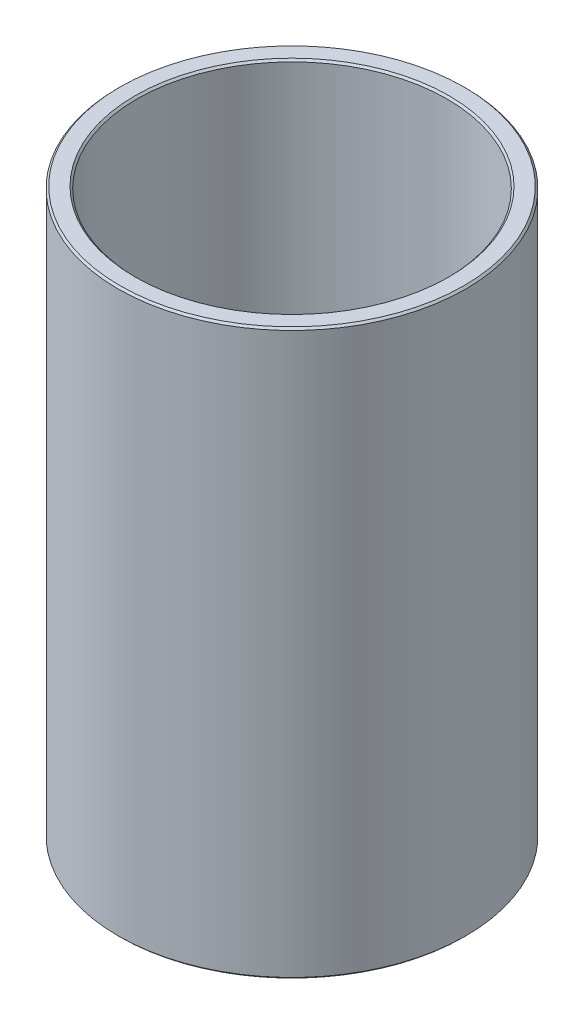
SolidWorks part; units mm, degrees
material "1.4305 (X8CrNiS18-9)"
ref_plane "Front Plane" through (0, 0, 0) normal (0, 0, 1) x (1, 0, 0)
ref_plane "Top Plane" through (0, 0, 0) normal (0, 1, 0) x (1, 0, 0)
ref_plane "Right Plane" through (0, 0, 0) normal (1, 0, 0) x (0, 0, -1)
other "Configuration Table"
sketch "Sketch1" plane through (0, 0, 0) normal (0, 0, 1) x (1, 0, 0)
  line L0 (0, 0) -> (16.5, 0) construction
  line L1 (16.5, 0) -> (18.5, 0)
  line L2 (18.5, 0) -> (18.5, 4)
  line L4 (18.5, 4) -> (18.5, 56)
  line L6 (18.5, 56) -> (18.5, 60)
  line L7 (18.5, 60) -> (16.5, 60)
  line L9 (0, 0) -> (0, 7.9023) construction
  line L10 (16.5, 60) -> (16.5, 56)
  line L12 (16.5, 56) -> (16.5, 4)
  line L14 (16.5, 4) -> (16.5, 0)
  dimension "Lip height" = 4
  dimension "Length" = 60
  dimension "ID" = 33
  dimension "OD" = 37
revolve "Revolve1" add sketch "Sketch1" angle 360 about L9
sketch "Sketch2" [suppressed] plane through (0, 0, 0) normal (1, 0, 0) x (0, 0, -1)
  line L0 (0, 88.5) -> (0, 64.0574) construction
  line L1 (3, 88.5) -> (3, 64.0574)
  line L2 (-3, 88.5) -> (-3, 64.0574)
  line L3 (-42.5, 92.5) -> (42.5, 92.5) construction
  line L4 (42.5, 4) -> (-42.5, 4) construction
  arc A0 (3, 88.5) -> (-3, 88.5) centre (0, 88.5) ccw
  arc A1 (-3, 64.0574) -> (3, 64.0574) centre (0, 64.0574) ccw
  point P3 (0, 76.2787)
  dimension "D1" = 6
  dimension "D2" = 4
  dimension "D3" = 60.0574
extrude "Cut-Extrude1" [suppressed] cut sketch "Sketch2" against normal through all
chamfer "Chamfer1" distance 0.2 angle 45 4 edges at (0, 0, -16.5) (0, 60, -16.5) (0, 60, -18.5) (0, 0, -18.5)
other "Save Bodies2" [suppressed]
other "Save Bodies3" [suppressed]
